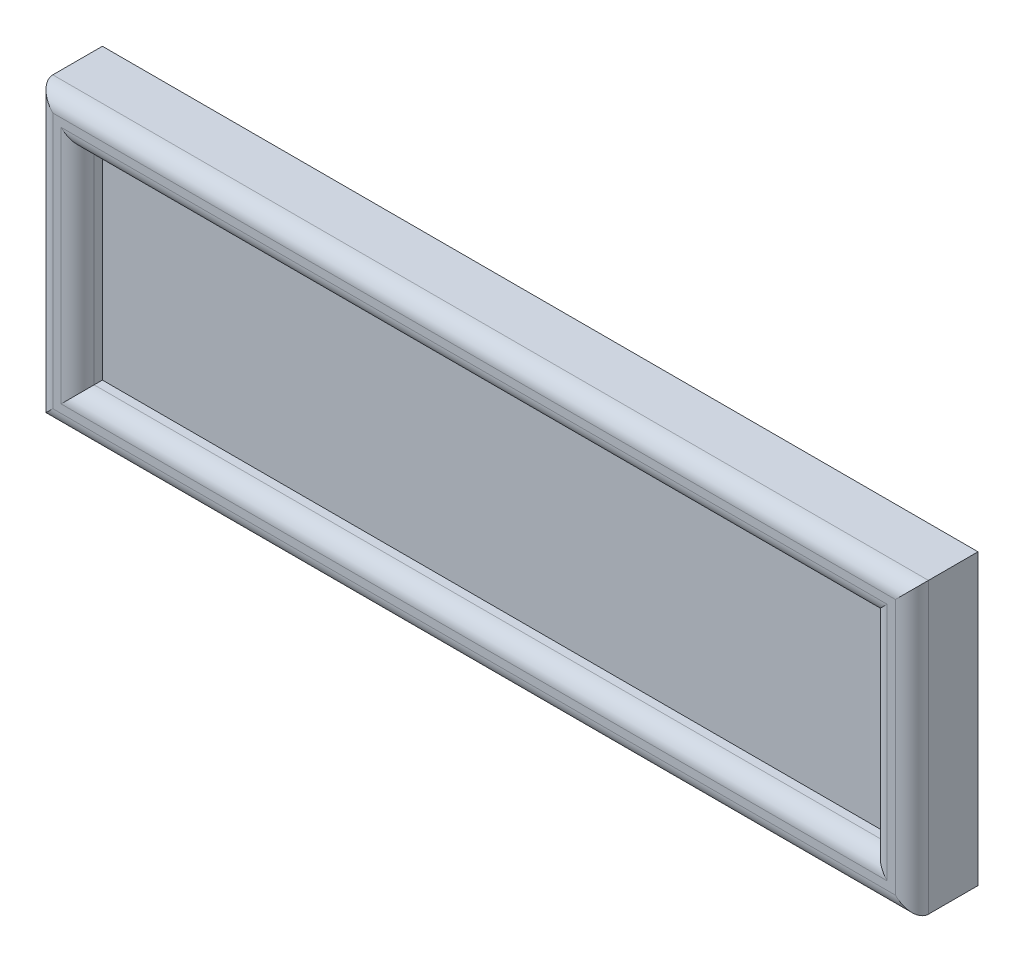
SolidWorks part; units mm, degrees
ref_plane "Спереди" through (0, 0, 0) normal (0, 0, 1) x (1, 0, 0)
ref_plane "Сверху" through (0, 0, 0) normal (0, 1, 0) x (1, 0, 0)
ref_plane "Справа" through (0, 0, 0) normal (1, 0, 0) x (0, 0, -1)
sketch "Эскиз1" plane through (0, 0, 0) normal (0, 0, 1) x (1, 0, 0)
  line L1 (26.5, -8.75) -> (-26.5, -8.75)
  line L2 (26.5, -8.75) -> (26.5, 8.75)
  line L3 (26.5, 8.75) -> (-26.5, 8.75)
  line L4 (-26.5, -8.75) -> (-26.5, 8.75)
  line L5 (0, 8.75) -> (0, -8.75) construction
  line L6 (26.5, 0) -> (-26.5, 0) construction
  point P0 (0, 0)
  dimension "D1" = 53
  dimension "D2" = 17.5
extrude "Бобышка-Вытянуть1" add sketch "Эскиз1" along normal mid plane 4
sketch "Эскиз3" plane through (0, 0, 0) normal (0, 0, 1) x (1, 0, 0)
  line L1 (25.5, -7.75) -> (-25.5, -7.75)
  line L2 (25.5, -7.75) -> (25.5, 7.75)
  line L3 (25.5, 7.75) -> (-25.5, 7.75)
  line L4 (-25.5, -7.75) -> (-25.5, 7.75)
  line L5 (0, 7.75) -> (0, -7.75) construction
  line L6 (25.5, 0) -> (-25.5, 0) construction
  point P0 (0, 0)
  dimension "D1" = 51
  dimension "D2" = 15.5
extrude "Вырез-Вытянуть2" cut sketch "Эскиз3" against normal mid plane 1
sketch "Эскиз2" plane through (0, 0, 2) normal (0, 0, 1) x (1, 0, 0)
  line L1 (24, -6.25) -> (-24, -6.25)
  line L2 (24, -6.25) -> (24, 6.25)
  line L3 (24, 6.25) -> (-24, 6.25)
  line L4 (-24, -6.25) -> (-24, 6.25)
  line L5 (0, 6.25) -> (0, -6.25) construction
  line L6 (24, 0) -> (-24, 0) construction
  point P0 (0, 0)
  dimension "D1" = 48
  dimension "D2" = 12.5
extrude "Вырез-Вытянуть3" cut sketch "Эскиз2" against normal blind 2
sketch "Эскиз4" plane through (0, 0, 0) normal (0, 0, 1) x (1, 0, 0)
  line L1 (-22.5, -7.75) -> (-25.5, -7.75)
  line L2 (-22.5, -7.75) -> (-22.5, 7.75)
  line L3 (-22.5, 7.75) -> (-25.5, 7.75)
  line L4 (-25.5, -7.75) -> (-25.5, 7.75)
  line L6 (-26.5, 8.75) -> (-26.5, -8.75) construction
  line L7 (-24, 6.25) -> (-24, -6.25) construction
  line L8 (26.5, 8.75) -> (-26.5, 8.75) construction
  point P9 (-25.5, 0)
  dimension "D1" = 1
  dimension "D2" = 1
  dimension "D3" = 1.5
extrude "Вырез-Вытянуть4" [suppressed] cut sketch "Эскиз4" along normal blind 2
fillet "Скругление1" radius 1 8 edges at (26.5, 0, 2) (0, 8.75, 2) (-26.5, 0, 2) (0, -8.75, 2) (0, -6.25, 2) (24, 0, 2) (0, 6.25, 2) (-24, 0, 2)
fillet "Скругление2" [suppressed] radius 1
sketch "Эскиз5" plane through (0, 0, 0) normal (1, 0, 0) x (0, 0, -1)
  line L0 (-0.1, -7.75) -> (0, -7.75)
  line L1 (-0.1, -7.75) -> (-0.1, 7.75)
  line L2 (0, -7.75) -> (0, 7.75)
  line L3 (-0.1, 7.75) -> (0, 7.75)
  line L4 (-0.1, -7.75) -> (0, 7.75) construction
  line L5 (0, -7.75) -> (-0.1, 7.75) construction
  point P0 (0, 0)
  point P1 (-0.05, 0)
  dimension "D1" = 15.5
  dimension "D2" = 0.1
extrude "Вырез-Вытянуть5" cut sketch "Эскиз5" against normal through all
